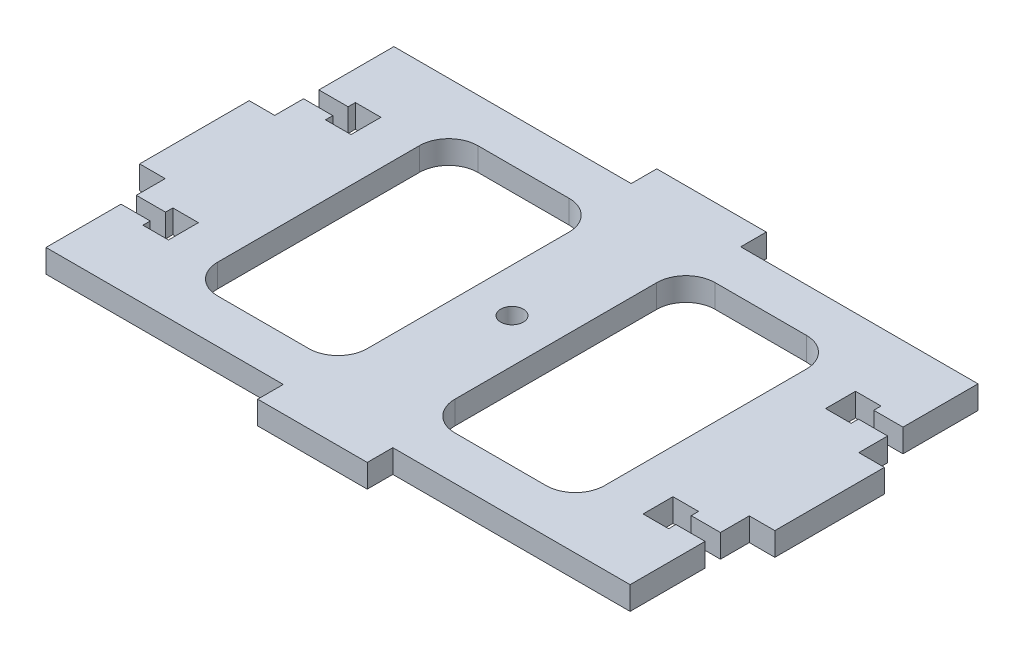
SolidWorks part; units mm, degrees
ref_plane "Front Plane" through (0, 0, 0) normal (0, 0, 1) x (1, 0, 0)
ref_plane "Top Plane" through (0, 0, 0) normal (0, 1, 0) x (1, 0, 0)
ref_plane "Right Plane" through (0, 0, 0) normal (1, 0, 0) x (0, 0, -1)
sketch "Sketch2" plane through (0, 0, 0) normal (0, 1, 0) x (1, 0, 0)
  line L0 (0, -1.7463) -> (0, 1.7463) construction
  line L1 (-40, 23.825) -> (40, 23.825)
  line L2 (-40, 23.825) -> (-40, -23.825)
  line L3 (-40, -23.825) -> (40, -23.825)
  line L4 (40, 23.825) -> (40, -23.825)
  point P4 (0, -23.825)
  dimension "D1" = 47.65
  dimension "D2" = 80
  dimension "D4" = 23.825
extrude "Boss-Extrude1" add sketch "Sketch2" along normal blind 3.175
sketch "Sketch3" plane through (0, 3.175, 0) normal (0, 1, 0) x (1, 0, 0)
  line L0 (40, 23.825) -> (-40, 23.825) construction
  line L1 (-7.5, 23.825) -> (7.5, 23.825)
  line L2 (-7.5, 23.825) -> (-7.5, 27.325)
  line L3 (-7.5, 27.325) -> (7.5, 27.325)
  line L4 (7.5, 23.825) -> (7.5, 27.325)
  point P6 (0, 23.825)
  dimension "D1" = 15
  dimension "D2" = 3.5
  dimension "D3" = 0
extrude "Boss-Extrude2" add sketch "Sketch3" against normal blind 3.175
sketch "Sketch4" plane through (0, 3.175, 0) normal (0, 1, 0) x (1, 0, 0)
  line L0 (-40, 23.825) -> (-40, -23.825) construction
  line L1 (-40, 7.5) -> (-43.5, 7.5)
  line L2 (-40, 7.5) -> (-40, -7.5)
  line L3 (-40, -7.5) -> (-43.5, -7.5)
  line L4 (-43.5, 7.5) -> (-43.5, -7.5)
  dimension "D1" = 15
  dimension "D2" = 3.5
  dimension "D3" = 7.5
extrude "Boss-Extrude3" add sketch "Sketch4" against normal blind 3.175
mirror "Mirror1" about plane through (0, 0, 0) normal (1, 0, 0) of "Boss-Extrude3"
mirror "Mirror2" about plane through (0, 0, 0) normal (0, 0, 1) of "Boss-Extrude2", "Mirror1"
sketch "Sketch5" plane through (0, 3.175, 0) normal (0, 1, 0) x (1, 0, 0)
  line L0 (-40, 13.55) -> (-36, 13.55)
  line L1 (-40, 23.825) -> (-40, 7.5) construction
  line L2 (-36, 13.55) -> (-36, 14.55)
  line L3 (-36, 14.55) -> (-32.5, 14.55)
  line L4 (-32.5, 14.55) -> (-32.5, 10.45)
  line L5 (-32.5, 10.45) -> (-36, 10.45)
  line L6 (-36, 10.45) -> (-36, 11.45)
  line L7 (-36, 11.45) -> (-40, 11.45)
  line L8 (-40, 11.45) -> (-40, 13.55)
  line L9 (-40, 7.5) -> (-43.5, 7.5) construction
  point P4 (-40, 12.5)
  dimension "D1" = 2.1
  dimension "D2" = 4.1
  dimension "D3" = 7.5
  dimension "D4" = 3.5
  dimension "D5" = 5
  dimension "D6" = 2.05
extrude "Cut-Extrude1" cut sketch "Sketch5" against normal blind 10
mirror "Mirror3" about plane through (0, 0, 0) normal (0, 0, 1) of "Cut-Extrude1"
mirror "Mirror4" about plane through (0, 0, 0) normal (1, 0, 0) of "Mirror3", "Cut-Extrude1"
sketch "Sketch7" plane through (0, 0, 0) normal (0, 1, 0) x (1, 0, 0)
  circle A0 centre (0, 0) radius 1.55
  dimension "D1" = 3.1
extrude "Cut-Extrude6" cut sketch "Sketch7" along normal through all both and the other way through all
sketch "Sketch8" plane through (0, 3.175, 0) normal (0, 1, 0) x (1, 0, 0)
  line L0 (-1.7463, 0) -> (1.7463, 0) construction
  line L1 (-22.5, 17.825) -> (-10, 17.825)
  line L2 (-26.5, 13.825) -> (-26.5, -13.825)
  line L3 (-22.5, -17.825) -> (-10, -17.825)
  line L4 (-6, 13.825) -> (-6, -13.825)
  line L5 (-26.5, 17.825) -> (-6, -17.825) construction
  line L6 (-26.5, -17.825) -> (-6, 17.825) construction
  line L7 (-32.5, 10.45) -> (-32.5, 14.55) construction
  line L8 (-7.5, 23.825) -> (-40, 23.825) construction
  line L9 (0, -1.7463) -> (0, 1.7463) construction
  line L10 (22.5, -17.825) -> (10, -17.825)
  line L11 (6, 13.825) -> (6, -13.825)
  line L12 (22.5, 17.825) -> (10, 17.825)
  line L13 (26.5, 13.825) -> (26.5, -13.825)
  arc A0 (-10, 17.825) -> (-6, 13.825) centre (-10, 13.825) cw
  arc A1 (-6, -13.825) -> (-10, -17.825) centre (-10, -13.825) cw
  arc A2 (-22.5, -17.825) -> (-26.5, -13.825) centre (-22.5, -13.825) cw
  arc A3 (-26.5, 13.825) -> (-22.5, 17.825) centre (-22.5, 13.825) cw
  arc A4 (6, -13.825) -> (10, -17.825) centre (10, -13.825) ccw
  arc A5 (10, 17.825) -> (6, 13.825) centre (10, 13.825) ccw
  arc A6 (22.5, -17.825) -> (26.5, -13.825) centre (22.5, -13.825) ccw
  arc A7 (26.5, 13.825) -> (22.5, 17.825) centre (22.5, 13.825) ccw
  point P0 (-16.25, 0)
  dimension "D4" = 4
  dimension "D1" = 6
  dimension "D2" = 6
  dimension "D3" = 6
extrude "Cut-Extrude7" cut sketch "Sketch8" against normal through all and the other way through all
